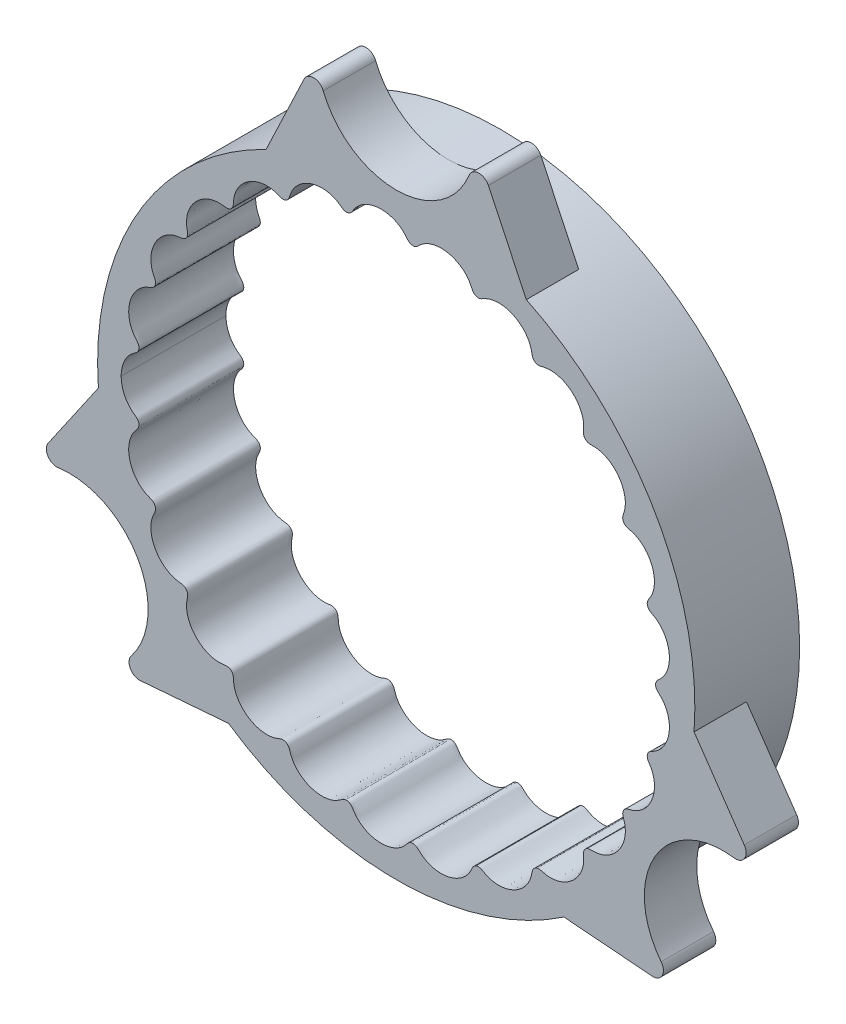
SolidWorks part; units mm, degrees
ref_plane "Plan de face" through (0, 0, 0) normal (0, 0, 1) x (1, 0, 0)
ref_plane "Plan de dessus" through (0, 0, 0) normal (0, 1, 0) x (1, 0, 0)
ref_plane "Plan de droite" through (0, 0, 0) normal (1, 0, 0) x (0, 0, -1)
sketch "Esquisse1" plane through (0, 0, 0) normal (0, 0, 1) x (1, 0, 0)
  line L0 (-1000, 0) -> (49000, 0) construction
  circle A1 centre (0, 0) radius 28.5
  spline S0 degree 4 poles (24.1426, 6.7991) (24.1177, 6.7609) (24.0692, 6.6836) (24.0004, 6.5645) (23.9483, 6.387) (23.9505, 6.1855) (24.0272, 5.9803) (24.1778, 5.8151) (24.3705, 5.7045) (24.5983, 5.5844) (24.8479, 5.4264) (25.1139, 5.2067) (25.3819, 4.9129) (25.6102, 4.583) (25.7961, 4.2235) (25.9371, 3.8403) (26.0305, 3.4429) (26.0756, 3.0373) (26.0716, 2.6291) (26.0179, 2.2244) (25.9151, 1.834) (25.7643, 1.4641) (25.5917, 1.1641) (25.4167, 0.9296) (25.2526, 0.7496) (25.1124, 0.6144) (24.9828, 0.4987) (24.8797, 0.3844) (24.8179, 0.2829) (24.7848, 0.2051) (24.7673, 0.1461) (24.7588, 0.1043) (24.7529, 0.0597) (24.7496, 0.0145) (24.7496, -0.0147) (24.7529, -0.06) (24.7589, -0.1048) (24.7675, -0.1468) (24.7852, -0.2061) (24.8185, -0.2842) (24.8808, -0.3859) (24.9847, -0.5005) (25.1148, -0.6166) (25.2554, -0.7525) (25.4198, -0.9333) (25.595, -1.1691) (25.7689, -1.4729) (25.9207, -1.8497) (26.0235, -2.2499) (26.0747, -2.6669) (26.0733, -3.0863) (26.0204, -3.5015) (25.917, -3.9063) (25.7644, -4.2943) (25.5662, -4.6548) (25.3259, -4.9815) (25.0816, -5.2331) (24.8519, -5.4186) (24.6671, -5.5402) (24.5395, -5.6139) (24.4102, -5.6846) (24.274, -5.758) (24.12, -5.8678) (23.9899, -6.0503) (23.9364, -6.2751) (23.9692, -6.4958) (24.0654, -6.6843) (24.1784, -6.8519) (24.2801, -7.019) (24.3936, -7.2353) (24.5034, -7.5077) (24.5951, -7.8454) (24.647, -8.2482) (24.6457, -8.6612) (24.576, -9.1855) (24.4176, -9.6961) (24.1747, -10.1766) (23.852, -10.6101) (23.5588, -10.9098) (23.241, -11.1578) (22.9466, -11.3291) (22.6921, -11.4408) (22.4727, -11.5135) (22.2939, -11.5615) (22.1013, -11.606) (21.9021, -11.6816) (21.7285, -11.8281) (21.6209, -12.0388) (21.6016, -12.2637) (21.6505, -12.4693) (21.7183, -12.6598) (21.7746, -12.8471) (21.8297, -13.085) (21.8672, -13.3762) (21.8707, -13.726) (21.8195, -14.1287) (21.7142, -14.528) (21.5148, -15.0178) (21.2331, -15.4721) (20.8771, -15.876) (20.4557, -16.2144) (20.0964, -16.4307) (19.7262, -16.5906) (19.3981, -16.6821) (19.1236, -16.7259) (18.8929, -16.7409) (18.7078, -16.7424) (18.5101, -16.7378) (18.2984, -16.7644) (18.0955, -16.8669) (17.9421, -17.0472) (17.8714, -17.2614) (17.8702, -17.4725) (17.8883, -17.6738) (17.8957, -17.8692) (17.8889, -18.1133) (17.8517, -18.4044) (17.7668, -18.7438) (17.6158, -19.1205) (17.4134, -19.4803) (17.1623, -19.8168) (16.8685, -20.1221) (16.5358, -20.3908) (16.1684, -20.6173) (15.771, -20.7957) (15.3688, -20.9145) (14.9702, -20.976) (14.6296, -20.9817) (14.3529, -20.9549) (14.1259, -20.9112) (13.9464, -20.866) (13.7558, -20.8128) (13.5435, -20.7889) (13.3222, -20.8417) (13.1314, -20.9817) (13.013, -21.1736) (12.9618, -21.3782) (12.9291, -21.5776) (12.887, -21.7685) (12.8188, -22.0029) (12.7093, -22.2752) (12.5416, -22.5821) (12.3006, -22.9086) (12.0142, -23.2057) (11.6866, -23.4682) (11.3255, -23.6897) (10.9359, -23.8661) (10.5233, -23.9928) (10.0937, -24.0655) (9.6744, -24.0792) (9.2731, -24.0382) (8.942, -23.9578) (8.6811, -23.862) (8.4724, -23.7624) (8.31, -23.6735) (8.1383, -23.575) (7.9372, -23.5018) (7.7049, -23.5021) (7.4781, -23.6007) (7.3169, -23.7729) (7.2208, -23.9706) (7.1156, -24.2034) (6.9743, -24.4604) (6.773, -24.7375) (6.4979, -25.0224) (6.1834, -25.2709) (5.8357, -25.4797) (5.4603, -25.6452) (5.0615, -25.7656) (4.6447, -25.8371) (4.2157, -25.8559) (3.7816, -25.8181) (3.3723, -25.7258) (2.9942, -25.5849) (2.6941, -25.4236) (2.4656, -25.2649) (2.2891, -25.1158) (2.1537, -24.9891) (2.0123, -24.8511) (1.8324, -24.7331) (1.553, -24.6659) (1.2621, -24.7546) (1.0754, -24.9576) (0.8891, -25.1941) (0.6967, -25.4018) (0.4476, -25.6153) (0.1257, -25.8218) (-0.2246, -25.9871) (-0.599, -26.1091) (-0.9909, -26.1853) (-1.3919, -26.2146) (-1.7962, -26.1958) (-2.1981, -26.1285) (-2.5915, -26.0119) (-2.9628, -25.849) (-3.3062, -25.6424) (-3.6154, -25.3948) (-3.8503, -25.1456) (-4.0231, -24.9087) (-4.157, -24.6911) (-4.2763, -24.5066) (-4.4563, -24.3545) (-4.6931, -24.2829) (-4.9238, -24.3097) (-5.115, -24.4061) (-5.2732, -24.5252) (-5.423, -24.6339) (-5.6174, -24.7592) (-5.864, -24.8876) (-6.1822, -25.0094) (-6.5751, -25.1011) (-6.9928, -25.1407) (-7.4281, -25.1231) (-7.8512, -25.0501) (-8.2556, -24.9263) (-8.636, -24.7563) (-8.9874, -24.5444) (-9.3058, -24.2932) (-9.5861, -24.0067) (-9.8229, -23.6892) (-9.9872, -23.3887) (-10.0948, -23.1158) (-10.1696, -22.8715) (-10.2411, -22.6635) (-10.3812, -22.4737) (-10.595, -22.3493) (-10.8256, -22.322) (-11.0338, -22.3709) (-11.2164, -22.4474) (-11.3887, -22.5149) (-11.6084, -22.5872) (-11.8793, -22.649) (-12.2179, -22.6866) (-12.6212, -22.6763) (-13.0353, -22.6095) (-13.4521, -22.4829) (-13.8453, -22.3049) (-14.2094, -22.0805) (-14.5395, -21.815) (-14.8313, -21.5131) (-15.0777, -21.1819) (-15.2753, -20.8275) (-15.4026, -20.5017) (-15.4765, -20.2177) (-15.5143, -19.9765) (-15.5318, -19.7817) (-15.5392, -19.5798) (-15.5656, -19.3704) (-15.6608, -19.166) (-15.8341, -19.0047) (-16.0476, -18.9266) (-16.2611, -18.9252) (-16.4568, -18.9543) (-16.6405, -18.9763) (-16.8713, -18.9908) (-17.1491, -18.9822) (-17.4862, -18.9332) (-17.8737, -18.8216) (-18.2576, -18.6527) (-18.6291, -18.4253) (-18.9648, -18.1541) (-19.2607, -17.8454) (-19.5135, -17.5053) (-19.7199, -17.1396) (-19.875, -16.7569) (-19.9769, -16.364) (-20.018, -16.0166) (-20.0178, -15.7231) (-19.9934, -15.4801) (-19.9613, -15.2872) (-19.9181, -15.0898) (-19.894, -14.8799) (-19.9394, -14.6589) (-20.0707, -14.462) (-20.2602, -14.3367) (-20.4672, -14.2852) (-20.6639, -14.2651) (-20.8473, -14.2402) (-21.0742, -14.196) (-21.3408, -14.1175) (-21.6546, -13.985) (-22.0015, -13.7794) (-22.3304, -13.5193) (-22.7055, -13.1302) (-23.0074, -12.6844) (-23.2291, -12.1981) (-23.3648, -11.6869) (-23.4186, -11.2774) (-23.4182, -10.8714) (-23.3703, -10.5248) (-23.296, -10.2407) (-23.211, -10.0117) (-23.1314, -9.8331) (-23.0402, -9.6526) (-22.9672, -9.4541) (-22.9601, -9.2287) (-23.0424, -9.0072) (-23.1982, -8.8407) (-23.3889, -8.7414) (-23.5777, -8.6723) (-23.7531, -8.5999) (-23.9662, -8.4963) (-24.2093, -8.3477) (-24.4803, -8.1356) (-24.7613, -7.8463) (-25.0085, -7.5133) (-25.2666, -7.049) (-25.4429, -6.5476) (-25.5339, -6.0256) (-25.5366, -5.4989) (-25.4855, -5.0889) (-25.3828, -4.696) (-25.2489, -4.3726) (-25.1052, -4.1164) (-24.9652, -3.9162) (-24.8431, -3.7634) (-24.7098, -3.6112) (-24.5919, -3.4354) (-24.5338, -3.2206) (-24.5604, -2.9926) (-24.6667, -2.797) (-24.8227, -2.6537) (-24.9897, -2.5393) (-25.1463, -2.4221) (-25.3325, -2.2638) (-25.5023, -2.0873) (-25.6545, -1.8958) (-25.7905, -1.6883) (-25.89, -1.512) (-25.979, -1.3255) (-26.0566, -1.1315) (-26.1214, -0.9307) (-26.1732, -0.7298) (-26.2073, -0.5457) (-26.2284, -0.3959) (-26.2405, -0.2557) (-26.247, -0.1691) (-26.2503, -0.0328) (-26.2503, 0.0323) (-26.2471, 0.1679) (-26.2407, 0.2542) (-26.2286, 0.3933) (-26.2078, 0.5423) (-26.1742, 0.7251) (-26.123, 0.925) (-26.0591, 1.1245) (-25.9824, 1.3176) (-25.8737, 1.547) (-25.7224, 1.8046) (-25.5451, 2.0414) (-25.3437, 2.2529) (-25.1596, 2.4115) (-25.0044, 2.5289) (-24.8386, 2.6423) (-24.6804, 2.7808) (-24.5546, 2.9935) (-24.5303, 3.2355) (-24.6, 3.4498) (-24.7118, 3.6094) (-24.804, 3.7191) (-24.9086, 3.8447) (-25.0204, 3.9911) (-25.1376, 4.1713) (-25.2521, 4.3886) (-25.3469, 4.6153) (-25.4409, 4.9075) (-25.515, 5.269) (-25.5464, 5.6988) (-25.509, 6.1899) (-25.401, 6.6704) (-25.2688, 7.0153) (-25.1588, 7.235) (-25.0985, 7.3418) knots 0 0 0 0 0 0.001685 0.003369 0.005054 0.006738 0.009006 0.011274 0.013086 0.014899 0.018524 0.022149 0.025774 0.029532 0.03329 0.037047 0.040805 0.044562 0.048319 0.052076 0.055834 0.059425 0.063017 0.064813 0.066609 0.068405 0.070201 0.071231 0.072261 0.072776 0.073291 0.073548 0.073806 0.074321 0.074838 0.075097 0.075356 0.075873 0.07639 0.077425 0.07846 0.080263 0.082066 0.083868 0.085671 0.089277 0.092883 0.09675 0.100617 0.104484 0.108351 0.112188 0.116026 0.119864 0.123701 0.127327 0.130952 0.132764 0.134577 0.135483 0.13639 0.138202 0.140296 0.142389 0.144459 0.146528 0.148331 0.150133 0.151935 0.153737 0.157342 0.160946 0.164812 0.168678 0.172544 0.180416 0.184421 0.188427 0.192432 0.195844 0.199256 0.200962 0.202668 0.204374 0.20608 0.208269 0.210458 0.212527 0.214596 0.216398 0.2182 0.220001 0.221803 0.225407 0.22901 0.232875 0.23674 0.240605 0.248477 0.252483 0.256489 0.260496 0.263908 0.26732 0.269026 0.270732 0.272438 0.274144 0.276335 0.278527 0.280595 0.282663 0.284464 0.286266 0.288067 0.289868 0.293471 0.297074 0.300938 0.304802 0.308666 0.31253 0.316537 0.320545 0.324552 0.328559 0.331971 0.335384 0.33709 0.338796 0.340502 0.342208 0.344401 0.346595 0.348662 0.350729 0.35253 0.354331 0.356132 0.357933 0.361536 0.365138 0.369001 0.372864 0.376727 0.38059 0.384598 0.388606 0.392614 0.396623 0.400035 0.403448 0.405154 0.40686 0.408567 0.410273 0.412468 0.414663 0.416905 0.419148 0.420948 0.422747 0.426346 0.429946 0.433545 0.437321 0.441097 0.444873 0.44865 0.452659 0.456668 0.460677 0.464686 0.468099 0.471512 0.473218 0.474925 0.476631 0.478338 0.480534 0.48273 0.48702 0.488749 0.490478 0.493937 0.497395 0.500854 0.50453 0.508207 0.511883 0.515559 0.519335 0.523111 0.526887 0.530662 0.534262 0.537861 0.54146 0.543259 0.545059 0.547301 0.549542 0.551738 0.553933 0.55564 0.557346 0.559053 0.560759 0.564172 0.567585 0.571593 0.575602 0.57961 0.583619 0.587396 0.591172 0.594949 0.598726 0.602325 0.605924 0.609523 0.611323 0.613123 0.615366 0.61761 0.619804 0.621998 0.623704 0.625411 0.627117 0.628823 0.632235 0.635648 0.639656 0.643663 0.647671 0.651679 0.655542 0.659406 0.663269 0.667133 0.670735 0.674338 0.676139 0.67794 0.679742 0.681543 0.68361 0.685678 0.68787 0.690063 0.691769 0.693475 0.695181 0.696887 0.700299 0.703711 0.707718 0.711725 0.715732 0.719739 0.723603 0.727468 0.731332 0.735197 0.7388 0.742403 0.744204 0.746006 0.747808 0.749609 0.751678 0.753746 0.755937 0.758127 0.759833 0.761539 0.763245 0.764951 0.768363 0.771775 0.775781 0.779787 0.783793 0.791664 0.795529 0.799395 0.80326 0.806864 0.810468 0.81227 0.814073 0.815875 0.817677 0.819746 0.821815 0.823999 0.826183 0.827931 0.82968 0.831429 0.833177 0.836675 0.840172 0.844094 0.848015 0.851937 0.859725 0.863591 0.867458 0.871324 0.874929 0.878534 0.880337 0.882139 0.883942 0.885745 0.887814 0.889884 0.891953 0.894023 0.895826 0.897629 0.899432 0.901235 0.904841 0.906644 0.908448 0.910381 0.912315 0.914249 0.916183 0.918117 0.92005 0.921017 0.921984 0.922951 0.923918 0.924879 0.925839 0.9268 0.927761 0.929682 0.931604 0.933525 0.935447 0.937368 0.93929 0.942875 0.94646 0.948253 0.950045 0.951838 0.95363 0.955683 0.957735 0.960756 0.962266 0.963777 0.964909 0.96604 0.968304 0.970568 0.972832 0.975095 0.977359 0.981887 0.986415 0.990943 0.995472 1 1 1 1 1 construction
  spline S1 degree 4 poles (24.75, 0) (24.75, -0.0119) (24.7507, -0.0298) (24.7529, -0.06) (24.7589, -0.1048) (24.7675, -0.1468) (24.7852, -0.2061) (24.8185, -0.2842) (24.8808, -0.3859) (24.9847, -0.5005) (25.1148, -0.6166) (25.2554, -0.7525) (25.4198, -0.9333) (25.595, -1.1691) (25.7689, -1.4729) (25.9207, -1.8497) (26.0235, -2.2499) (26.0747, -2.6669) (26.0733, -3.0863) (26.0204, -3.5015) (25.917, -3.9063) (25.7644, -4.2943) (25.5662, -4.6548) (25.3259, -4.9815) (25.0816, -5.2331) (24.8519, -5.4186) (24.6671, -5.5402) (24.5395, -5.6139) (24.4102, -5.6846) (24.274, -5.758) (24.12, -5.8678) (23.9899, -6.0503) (23.9364, -6.2751) (23.9692, -6.4958) (24.0654, -6.6843) (24.1784, -6.8519) (24.2801, -7.019) (24.3936, -7.2353) (24.5034, -7.5077) (24.5951, -7.8454) (24.647, -8.2482) (24.6457, -8.6612) (24.576, -9.1855) (24.4176, -9.6961) (24.1747, -10.1766) (23.852, -10.6101) (23.5588, -10.9098) (23.241, -11.1578) (22.9466, -11.3291) (22.6921, -11.4408) (22.4727, -11.5135) (22.2939, -11.5615) (22.1013, -11.606) (21.9021, -11.6816) (21.7285, -11.8281) (21.6209, -12.0388) (21.6016, -12.2637) (21.6505, -12.4693) (21.7183, -12.6598) (21.7746, -12.8471) (21.8297, -13.085) (21.8672, -13.3762) (21.8707, -13.726) (21.8195, -14.1287) (21.7142, -14.528) (21.5148, -15.0178) (21.2331, -15.4721) (20.8771, -15.876) (20.4557, -16.2144) (20.0964, -16.4307) (19.7262, -16.5906) (19.3981, -16.6821) (19.1236, -16.7259) (18.8929, -16.7409) (18.7078, -16.7424) (18.5101, -16.7378) (18.2984, -16.7644) (18.0955, -16.8669) (17.9421, -17.0472) (17.8714, -17.2614) (17.8702, -17.4725) (17.8883, -17.6738) (17.8957, -17.8692) (17.8889, -18.1133) (17.8517, -18.4044) (17.7668, -18.7438) (17.6158, -19.1205) (17.4134, -19.4803) (17.1623, -19.8168) (16.8685, -20.1221) (16.5358, -20.3908) (16.1684, -20.6173) (15.771, -20.7957) (15.3688, -20.9145) (14.9702, -20.976) (14.6296, -20.9817) (14.3529, -20.9549) (14.1259, -20.9112) (13.9464, -20.866) (13.7558, -20.8128) (13.5435, -20.7889) (13.3222, -20.8417) (13.1314, -20.9817) (13.013, -21.1736) (12.9618, -21.3782) (12.9291, -21.5776) (12.887, -21.7685) (12.8188, -22.0029) (12.7093, -22.2752) (12.5416, -22.5821) (12.3006, -22.9086) (12.0142, -23.2057) (11.6866, -23.4682) (11.3255, -23.6897) (10.9359, -23.8661) (10.5233, -23.9928) (10.0937, -24.0655) (9.6744, -24.0792) (9.2731, -24.0382) (8.942, -23.9578) (8.6811, -23.862) (8.4724, -23.7624) (8.31, -23.6735) (8.1383, -23.575) (7.9372, -23.5018) (7.7049, -23.5021) (7.4781, -23.6007) (7.3169, -23.7729) (7.2208, -23.9706) (7.1156, -24.2034) (6.9743, -24.4604) (6.773, -24.7375) (6.4979, -25.0224) (6.1834, -25.2709) (5.8357, -25.4797) (5.4603, -25.6452) (5.0615, -25.7656) (4.6447, -25.8371) (4.2157, -25.8559) (3.7816, -25.8181) (3.3723, -25.7258) (2.9942, -25.5849) (2.6941, -25.4236) (2.4656, -25.2649) (2.2891, -25.1158) (2.1537, -24.9891) (2.0123, -24.8511) (1.8324, -24.7331) (1.553, -24.6659) (1.2621, -24.7546) (1.0754, -24.9576) (0.8891, -25.1941) (0.6967, -25.4018) (0.4476, -25.6153) (0.1257, -25.8218) (-0.2246, -25.9871) (-0.599, -26.1091) (-0.9909, -26.1853) (-1.3919, -26.2146) (-1.7962, -26.1958) (-2.1981, -26.1285) (-2.5915, -26.0119) (-2.9628, -25.849) (-3.3062, -25.6424) (-3.6154, -25.3948) (-3.8503, -25.1456) (-4.0231, -24.9087) (-4.157, -24.6911) (-4.2763, -24.5066) (-4.4563, -24.3545) (-4.6931, -24.2829) (-4.9238, -24.3097) (-5.115, -24.4061) (-5.2732, -24.5252) (-5.423, -24.6339) (-5.6174, -24.7592) (-5.864, -24.8876) (-6.1822, -25.0094) (-6.5751, -25.1011) (-6.9928, -25.1407) (-7.4281, -25.1231) (-7.8512, -25.0501) (-8.2556, -24.9263) (-8.636, -24.7563) (-8.9874, -24.5444) (-9.3058, -24.2932) (-9.5861, -24.0067) (-9.8229, -23.6892) (-9.9872, -23.3887) (-10.0948, -23.1158) (-10.1696, -22.8715) (-10.2411, -22.6635) (-10.3812, -22.4737) (-10.595, -22.3493) (-10.8256, -22.322) (-11.0338, -22.3709) (-11.2164, -22.4474) (-11.3887, -22.5149) (-11.6084, -22.5872) (-11.8793, -22.649) (-12.2179, -22.6866) (-12.6212, -22.6763) (-13.0353, -22.6095) (-13.4521, -22.4829) (-13.8453, -22.3049) (-14.2094, -22.0805) (-14.5395, -21.815) (-14.8313, -21.5131) (-15.0777, -21.1819) (-15.2753, -20.8275) (-15.4026, -20.5017) (-15.4765, -20.2177) (-15.5143, -19.9765) (-15.5318, -19.7817) (-15.5392, -19.5798) (-15.5656, -19.3704) (-15.6608, -19.166) (-15.8341, -19.0047) (-16.0476, -18.9266) (-16.2611, -18.9252) (-16.4568, -18.9543) (-16.6405, -18.9763) (-16.8713, -18.9908) (-17.1491, -18.9822) (-17.4862, -18.9332) (-17.8737, -18.8216) (-18.2576, -18.6527) (-18.6291, -18.4253) (-18.9648, -18.1541) (-19.2607, -17.8454) (-19.5135, -17.5053) (-19.7199, -17.1396) (-19.875, -16.7569) (-19.9769, -16.364) (-20.018, -16.0166) (-20.0178, -15.7231) (-19.9934, -15.4801) (-19.9613, -15.2872) (-19.9181, -15.0898) (-19.894, -14.8799) (-19.9394, -14.6589) (-20.0707, -14.462) (-20.2602, -14.3367) (-20.4672, -14.2852) (-20.6639, -14.2651) (-20.8473, -14.2402) (-21.0742, -14.196) (-21.3408, -14.1175) (-21.6546, -13.985) (-22.0015, -13.7794) (-22.3304, -13.5193) (-22.7055, -13.1302) (-23.0074, -12.6844) (-23.2291, -12.1981) (-23.3648, -11.6869) (-23.4186, -11.2774) (-23.4182, -10.8714) (-23.3703, -10.5248) (-23.296, -10.2407) (-23.211, -10.0117) (-23.1314, -9.8331) (-23.0402, -9.6526) (-22.9672, -9.4541) (-22.9601, -9.2287) (-23.0424, -9.0072) (-23.1982, -8.8407) (-23.3889, -8.7414) (-23.5777, -8.6723) (-23.7531, -8.5999) (-23.9662, -8.4963) (-24.2093, -8.3477) (-24.4803, -8.1356) (-24.7613, -7.8463) (-25.0085, -7.5133) (-25.2666, -7.049) (-25.4429, -6.5476) (-25.5339, -6.0256) (-25.5366, -5.4989) (-25.4855, -5.0889) (-25.3828, -4.696) (-25.2489, -4.3726) (-25.1052, -4.1164) (-24.9652, -3.9162) (-24.8431, -3.7634) (-24.7098, -3.6112) (-24.5919, -3.4354) (-24.5338, -3.2206) (-24.5604, -2.9926) (-24.6667, -2.797) (-24.8227, -2.6537) (-24.9897, -2.5393) (-25.1463, -2.4221) (-25.3325, -2.2638) (-25.5023, -2.0873) (-25.6545, -1.8958) (-25.7905, -1.6883) (-25.89, -1.512) (-25.979, -1.3255) (-26.0566, -1.1315) (-26.1214, -0.9307) (-26.1732, -0.7298) (-26.2073, -0.5457) (-26.2284, -0.3959) (-26.2405, -0.2557) (-26.247, -0.1691) (-26.2495, -0.0667) (-26.25, -0.0223) (-26.25, 0) knots 0.074321 0.074321 0.074321 0.074321 0.074321 0.074838 0.075097 0.075356 0.075873 0.07639 0.077425 0.07846 0.080263 0.082066 0.083868 0.085671 0.089277 0.092883 0.09675 0.100617 0.104484 0.108351 0.112188 0.116026 0.119864 0.123701 0.127327 0.130952 0.132764 0.134577 0.135483 0.13639 0.138202 0.140296 0.142389 0.144459 0.146528 0.148331 0.150133 0.151935 0.153737 0.157342 0.160946 0.164812 0.168678 0.172544 0.180416 0.184421 0.188427 0.192432 0.195844 0.199256 0.200962 0.202668 0.204374 0.20608 0.208269 0.210458 0.212527 0.214596 0.216398 0.2182 0.220001 0.221803 0.225407 0.22901 0.232875 0.23674 0.240605 0.248477 0.252483 0.256489 0.260496 0.263908 0.26732 0.269026 0.270732 0.272438 0.274144 0.276335 0.278527 0.280595 0.282663 0.284464 0.286266 0.288067 0.289868 0.293471 0.297074 0.300938 0.304802 0.308666 0.31253 0.316537 0.320545 0.324552 0.328559 0.331971 0.335384 0.33709 0.338796 0.340502 0.342208 0.344401 0.346595 0.348662 0.350729 0.35253 0.354331 0.356132 0.357933 0.361536 0.365138 0.369001 0.372864 0.376727 0.38059 0.384598 0.388606 0.392614 0.396623 0.400035 0.403448 0.405154 0.40686 0.408567 0.410273 0.412468 0.414663 0.416905 0.419148 0.420948 0.422747 0.426346 0.429946 0.433545 0.437321 0.441097 0.444873 0.44865 0.452659 0.456668 0.460677 0.464686 0.468099 0.471512 0.473218 0.474925 0.476631 0.478338 0.480534 0.48273 0.48702 0.488749 0.490478 0.493937 0.497395 0.500854 0.50453 0.508207 0.511883 0.515559 0.519335 0.523111 0.526887 0.530662 0.534262 0.537861 0.54146 0.543259 0.545059 0.547301 0.549542 0.551738 0.553933 0.55564 0.557346 0.559053 0.560759 0.564172 0.567585 0.571593 0.575602 0.57961 0.583619 0.587396 0.591172 0.594949 0.598726 0.602325 0.605924 0.609523 0.611323 0.613123 0.615366 0.61761 0.619804 0.621998 0.623704 0.625411 0.627117 0.628823 0.632235 0.635648 0.639656 0.643663 0.647671 0.651679 0.655542 0.659406 0.663269 0.667133 0.670735 0.674338 0.676139 0.67794 0.679742 0.681543 0.68361 0.685678 0.68787 0.690063 0.691769 0.693475 0.695181 0.696887 0.700299 0.703711 0.707718 0.711725 0.715732 0.719739 0.723603 0.727468 0.731332 0.735197 0.7388 0.742403 0.744204 0.746006 0.747808 0.749609 0.751678 0.753746 0.755937 0.758127 0.759833 0.761539 0.763245 0.764951 0.768363 0.771775 0.775781 0.779787 0.783793 0.791664 0.795529 0.799395 0.80326 0.806864 0.810468 0.81227 0.814073 0.815875 0.817677 0.819746 0.821815 0.823999 0.826183 0.827931 0.82968 0.831429 0.833177 0.836675 0.840172 0.844094 0.848015 0.851937 0.859725 0.863591 0.867458 0.871324 0.874929 0.878534 0.880337 0.882139 0.883942 0.885745 0.887814 0.889884 0.891953 0.894023 0.895826 0.897629 0.899432 0.901235 0.904841 0.906644 0.908448 0.910381 0.912315 0.914249 0.916183 0.918117 0.92005 0.921017 0.921984 0.922951 0.923918 0.923918 0.923918 0.923918 0.923918
  spline S2 degree 4 poles (24.75, 0) (24.75, 0.0119) (24.7507, 0.0298) (24.7529, 0.06) (24.7589, 0.1048) (24.7675, 0.1468) (24.7852, 0.2061) (24.8185, 0.2842) (24.8808, 0.3859) (24.9847, 0.5005) (25.1148, 0.6166) (25.2554, 0.7525) (25.4198, 0.9333) (25.595, 1.1691) (25.7689, 1.4729) (25.9207, 1.8497) (26.0235, 2.2499) (26.0747, 2.6669) (26.0733, 3.0863) (26.0204, 3.5015) (25.917, 3.9063) (25.7644, 4.2943) (25.5662, 4.6548) (25.3259, 4.9815) (25.0816, 5.2331) (24.8519, 5.4186) (24.6671, 5.5402) (24.5395, 5.6139) (24.4102, 5.6846) (24.274, 5.758) (24.12, 5.8678) (23.9899, 6.0503) (23.9364, 6.2751) (23.9692, 6.4958) (24.0654, 6.6843) (24.1784, 6.8519) (24.2801, 7.019) (24.3936, 7.2353) (24.5034, 7.5077) (24.5951, 7.8454) (24.647, 8.2482) (24.6457, 8.6612) (24.576, 9.1855) (24.4176, 9.6961) (24.1747, 10.1766) (23.852, 10.6101) (23.5588, 10.9098) (23.241, 11.1578) (22.9466, 11.3291) (22.6921, 11.4408) (22.4727, 11.5135) (22.2939, 11.5615) (22.1013, 11.606) (21.9021, 11.6816) (21.7285, 11.8281) (21.6209, 12.0388) (21.6016, 12.2637) (21.6505, 12.4693) (21.7183, 12.6598) (21.7746, 12.8471) (21.8297, 13.085) (21.8672, 13.3762) (21.8707, 13.726) (21.8195, 14.1287) (21.7142, 14.528) (21.5148, 15.0178) (21.2331, 15.4721) (20.8771, 15.876) (20.4557, 16.2144) (20.0964, 16.4307) (19.7262, 16.5906) (19.3981, 16.6821) (19.1236, 16.7259) (18.8929, 16.7409) (18.7078, 16.7424) (18.5101, 16.7378) (18.2984, 16.7644) (18.0955, 16.8669) (17.9421, 17.0472) (17.8714, 17.2614) (17.8702, 17.4725) (17.8883, 17.6738) (17.8957, 17.8692) (17.8889, 18.1133) (17.8517, 18.4044) (17.7668, 18.7438) (17.6158, 19.1205) (17.4134, 19.4803) (17.1623, 19.8168) (16.8685, 20.1221) (16.5358, 20.3908) (16.1684, 20.6173) (15.771, 20.7957) (15.3688, 20.9145) (14.9702, 20.976) (14.6296, 20.9817) (14.3529, 20.9549) (14.1259, 20.9112) (13.9464, 20.866) (13.7558, 20.8128) (13.5435, 20.7889) (13.3222, 20.8417) (13.1314, 20.9817) (13.013, 21.1736) (12.9618, 21.3782) (12.9291, 21.5776) (12.887, 21.7685) (12.8188, 22.0029) (12.7093, 22.2752) (12.5416, 22.5821) (12.3006, 22.9086) (12.0142, 23.2057) (11.6866, 23.4682) (11.3255, 23.6897) (10.9359, 23.8661) (10.5233, 23.9928) (10.0937, 24.0655) (9.6744, 24.0792) (9.2731, 24.0382) (8.942, 23.9578) (8.6811, 23.862) (8.4724, 23.7624) (8.31, 23.6735) (8.1383, 23.575) (7.9372, 23.5018) (7.7049, 23.5021) (7.4781, 23.6007) (7.3169, 23.7729) (7.2208, 23.9706) (7.1156, 24.2034) (6.9743, 24.4604) (6.773, 24.7375) (6.4979, 25.0224) (6.1834, 25.2709) (5.8357, 25.4797) (5.4603, 25.6452) (5.0615, 25.7656) (4.6447, 25.8371) (4.2157, 25.8559) (3.7816, 25.8181) (3.3723, 25.7258) (2.9942, 25.5849) (2.6941, 25.4236) (2.4656, 25.2649) (2.2891, 25.1158) (2.1537, 24.9891) (2.0123, 24.8511) (1.8324, 24.7331) (1.553, 24.6659) (1.2621, 24.7546) (1.0754, 24.9576) (0.8891, 25.1941) (0.6967, 25.4018) (0.4476, 25.6153) (0.1257, 25.8218) (-0.2246, 25.9871) (-0.599, 26.1091) (-0.9909, 26.1853) (-1.3919, 26.2146) (-1.7962, 26.1958) (-2.1981, 26.1285) (-2.5915, 26.0119) (-2.9628, 25.849) (-3.3062, 25.6424) (-3.6154, 25.3948) (-3.8503, 25.1456) (-4.0231, 24.9087) (-4.157, 24.6911) (-4.2763, 24.5066) (-4.4563, 24.3545) (-4.6931, 24.2829) (-4.9238, 24.3097) (-5.115, 24.4061) (-5.2732, 24.5252) (-5.423, 24.6339) (-5.6174, 24.7592) (-5.864, 24.8876) (-6.1822, 25.0094) (-6.5751, 25.1011) (-6.9928, 25.1407) (-7.4281, 25.1231) (-7.8512, 25.0501) (-8.2556, 24.9263) (-8.636, 24.7563) (-8.9874, 24.5444) (-9.3058, 24.2932) (-9.5861, 24.0067) (-9.8229, 23.6892) (-9.9872, 23.3887) (-10.0948, 23.1158) (-10.1696, 22.8715) (-10.2411, 22.6635) (-10.3812, 22.4737) (-10.595, 22.3493) (-10.8256, 22.322) (-11.0338, 22.3709) (-11.2164, 22.4474) (-11.3887, 22.5149) (-11.6084, 22.5872) (-11.8793, 22.649) (-12.2179, 22.6866) (-12.6212, 22.6763) (-13.0353, 22.6095) (-13.4521, 22.4829) (-13.8453, 22.3049) (-14.2094, 22.0805) (-14.5395, 21.815) (-14.8313, 21.5131) (-15.0777, 21.1819) (-15.2753, 20.8275) (-15.4026, 20.5017) (-15.4765, 20.2177) (-15.5143, 19.9765) (-15.5318, 19.7817) (-15.5392, 19.5798) (-15.5656, 19.3704) (-15.6608, 19.166) (-15.8341, 19.0047) (-16.0476, 18.9266) (-16.2611, 18.9252) (-16.4568, 18.9543) (-16.6405, 18.9763) (-16.8713, 18.9908) (-17.1491, 18.9822) (-17.4862, 18.9332) (-17.8737, 18.8216) (-18.2576, 18.6527) (-18.6291, 18.4253) (-18.9648, 18.1541) (-19.2607, 17.8454) (-19.5135, 17.5053) (-19.7199, 17.1396) (-19.875, 16.7569) (-19.9769, 16.364) (-20.018, 16.0166) (-20.0178, 15.7231) (-19.9934, 15.4801) (-19.9613, 15.2872) (-19.9181, 15.0898) (-19.894, 14.8799) (-19.9394, 14.6589) (-20.0707, 14.462) (-20.2602, 14.3367) (-20.4672, 14.2852) (-20.6639, 14.2651) (-20.8473, 14.2402) (-21.0742, 14.196) (-21.3408, 14.1175) (-21.6546, 13.985) (-22.0015, 13.7794) (-22.3304, 13.5193) (-22.7055, 13.1302) (-23.0074, 12.6844) (-23.2291, 12.1981) (-23.3648, 11.6869) (-23.4186, 11.2774) (-23.4182, 10.8714) (-23.3703, 10.5248) (-23.296, 10.2407) (-23.211, 10.0117) (-23.1314, 9.8331) (-23.0402, 9.6526) (-22.9672, 9.4541) (-22.9601, 9.2287) (-23.0424, 9.0072) (-23.1982, 8.8407) (-23.3889, 8.7414) (-23.5777, 8.6723) (-23.7531, 8.5999) (-23.9662, 8.4963) (-24.2093, 8.3477) (-24.4803, 8.1356) (-24.7613, 7.8463) (-25.0085, 7.5133) (-25.2666, 7.049) (-25.4429, 6.5476) (-25.5339, 6.0256) (-25.5366, 5.4989) (-25.4855, 5.0889) (-25.3828, 4.696) (-25.2489, 4.3726) (-25.1052, 4.1164) (-24.9652, 3.9162) (-24.8431, 3.7634) (-24.7098, 3.6112) (-24.5919, 3.4354) (-24.5338, 3.2206) (-24.5604, 2.9926) (-24.6667, 2.797) (-24.8227, 2.6537) (-24.9897, 2.5393) (-25.1463, 2.4221) (-25.3325, 2.2638) (-25.5023, 2.0873) (-25.6545, 1.8958) (-25.7905, 1.6883) (-25.89, 1.512) (-25.979, 1.3255) (-26.0566, 1.1315) (-26.1214, 0.9307) (-26.1732, 0.7298) (-26.2073, 0.5457) (-26.2284, 0.3959) (-26.2405, 0.2557) (-26.247, 0.1691) (-26.2495, 0.0667) (-26.25, 0.0223) (-26.25, 0) knots 0.074321 0.074321 0.074321 0.074321 0.074321 0.074838 0.075097 0.075356 0.075873 0.07639 0.077425 0.07846 0.080263 0.082066 0.083868 0.085671 0.089277 0.092883 0.09675 0.100617 0.104484 0.108351 0.112188 0.116026 0.119864 0.123701 0.127327 0.130952 0.132764 0.134577 0.135483 0.13639 0.138202 0.140296 0.142389 0.144459 0.146528 0.148331 0.150133 0.151935 0.153737 0.157342 0.160946 0.164812 0.168678 0.172544 0.180416 0.184421 0.188427 0.192432 0.195844 0.199256 0.200962 0.202668 0.204374 0.20608 0.208269 0.210458 0.212527 0.214596 0.216398 0.2182 0.220001 0.221803 0.225407 0.22901 0.232875 0.23674 0.240605 0.248477 0.252483 0.256489 0.260496 0.263908 0.26732 0.269026 0.270732 0.272438 0.274144 0.276335 0.278527 0.280595 0.282663 0.284464 0.286266 0.288067 0.289868 0.293471 0.297074 0.300938 0.304802 0.308666 0.31253 0.316537 0.320545 0.324552 0.328559 0.331971 0.335384 0.33709 0.338796 0.340502 0.342208 0.344401 0.346595 0.348662 0.350729 0.35253 0.354331 0.356132 0.357933 0.361536 0.365138 0.369001 0.372864 0.376727 0.38059 0.384598 0.388606 0.392614 0.396623 0.400035 0.403448 0.405154 0.40686 0.408567 0.410273 0.412468 0.414663 0.416905 0.419148 0.420948 0.422747 0.426346 0.429946 0.433545 0.437321 0.441097 0.444873 0.44865 0.452659 0.456668 0.460677 0.464686 0.468099 0.471512 0.473218 0.474925 0.476631 0.478338 0.480534 0.48273 0.48702 0.488749 0.490478 0.493937 0.497395 0.500854 0.50453 0.508207 0.511883 0.515559 0.519335 0.523111 0.526887 0.530662 0.534262 0.537861 0.54146 0.543259 0.545059 0.547301 0.549542 0.551738 0.553933 0.55564 0.557346 0.559053 0.560759 0.564172 0.567585 0.571593 0.575602 0.57961 0.583619 0.587396 0.591172 0.594949 0.598726 0.602325 0.605924 0.609523 0.611323 0.613123 0.615366 0.61761 0.619804 0.621998 0.623704 0.625411 0.627117 0.628823 0.632235 0.635648 0.639656 0.643663 0.647671 0.651679 0.655542 0.659406 0.663269 0.667133 0.670735 0.674338 0.676139 0.67794 0.679742 0.681543 0.68361 0.685678 0.68787 0.690063 0.691769 0.693475 0.695181 0.696887 0.700299 0.703711 0.707718 0.711725 0.715732 0.719739 0.723603 0.727468 0.731332 0.735197 0.7388 0.742403 0.744204 0.746006 0.747808 0.749609 0.751678 0.753746 0.755937 0.758127 0.759833 0.761539 0.763245 0.764951 0.768363 0.771775 0.775781 0.779787 0.783793 0.791664 0.795529 0.799395 0.80326 0.806864 0.810468 0.81227 0.814073 0.815875 0.817677 0.819746 0.821815 0.823999 0.826183 0.827931 0.82968 0.831429 0.833177 0.836675 0.840172 0.844094 0.848015 0.851937 0.859725 0.863591 0.867458 0.871324 0.874929 0.878534 0.880337 0.882139 0.883942 0.885745 0.887814 0.889884 0.891953 0.894023 0.895826 0.897629 0.899432 0.901235 0.904841 0.906644 0.908448 0.910381 0.912315 0.914249 0.916183 0.918117 0.92005 0.921017 0.921984 0.922951 0.923918 0.923918 0.923918 0.923918 0.923918
  dimension "D1" = 57
extrude "Boss.-Extru.1" add sketch "Esquisse1" along normal blind 10
sketch "Esquisse2" plane through (0, 0, 10) normal (0, 0, 1) x (1, 0, 0)
  line L0 (-8.7957, 33.2737) -> (-12.418, 25.6524)
  line L1 (0, -1000) -> (0, 49000) construction
  line L2 (8.7957, 33.2737) -> (12.418, 25.6524)
  line L3 (33.2138, -9.0195) -> (28.4246, -2.0719)
  line L4 (24.418, -24.2542) -> (16.0066, -23.5805)
  line L5 (-24.418, -24.2542) -> (-16.0066, -23.5805)
  line L6 (-33.2138, -9.0195) -> (-28.4246, -2.0719)
  circle A0 centre (0, 0) radius 28.5
  arc A1 (-6.964, 33.2157) -> (6.964, 33.2157) centre (0, 36) ccw
  arc A2 (-8.7957, 33.2737) -> (-6.964, 33.2157) centre (-7.8926, 32.8445) cw
  circle A3 centre (0, 0) radius 28.5 construction
  arc A4 (8.7957, 33.2737) -> (6.964, 33.2157) centre (7.8926, 32.8445) ccw
  arc A5 (32.2476, -10.5768) -> (25.2836, -22.6389) centre (31.1769, -18) ccw
  arc A6 (33.2138, -9.0195) -> (32.2476, -10.5768) centre (32.3904, -9.5871) cw
  arc A7 (24.418, -24.2542) -> (25.2836, -22.6389) centre (24.4978, -23.2574) ccw
  arc A8 (-25.2836, -22.6389) -> (-32.2476, -10.5768) centre (-31.1769, -18) ccw
  arc A9 (-24.418, -24.2542) -> (-25.2836, -22.6389) centre (-24.4978, -23.2574) cw
  arc A10 (-33.2138, -9.0195) -> (-32.2476, -10.5768) centre (-32.3904, -9.5871) ccw
  point P9 (-7.5, 36)
  point P37 (0, 0)
  circle M4 centre (0, 0) radius 28.5
  dimension "D1" = 15
  dimension "D2" = 1
  dimension "D3" = 3
extrude "Boss.-Extru.2" add sketch "Esquisse2" against normal blind 5 contours A2 L0 A0 A1 | L2 A4 A1 M4 | A6 L3 A0 A5 | L4 A7 A5 M4 | A9 L5 A0 A8 | L6 A10 A8 M4
equation "\"R\"= 26'Radius of the rotor"
equation "\"E\"= 0.75'Eccentricity from input shaft to center of rotor"
equation "\"Rr\"= 0.5'Roller radius"
equation "\"N\"= 26'Amount of rollers"
equation "\"D1@Esquisse1\"=\"R\"*2+5"
